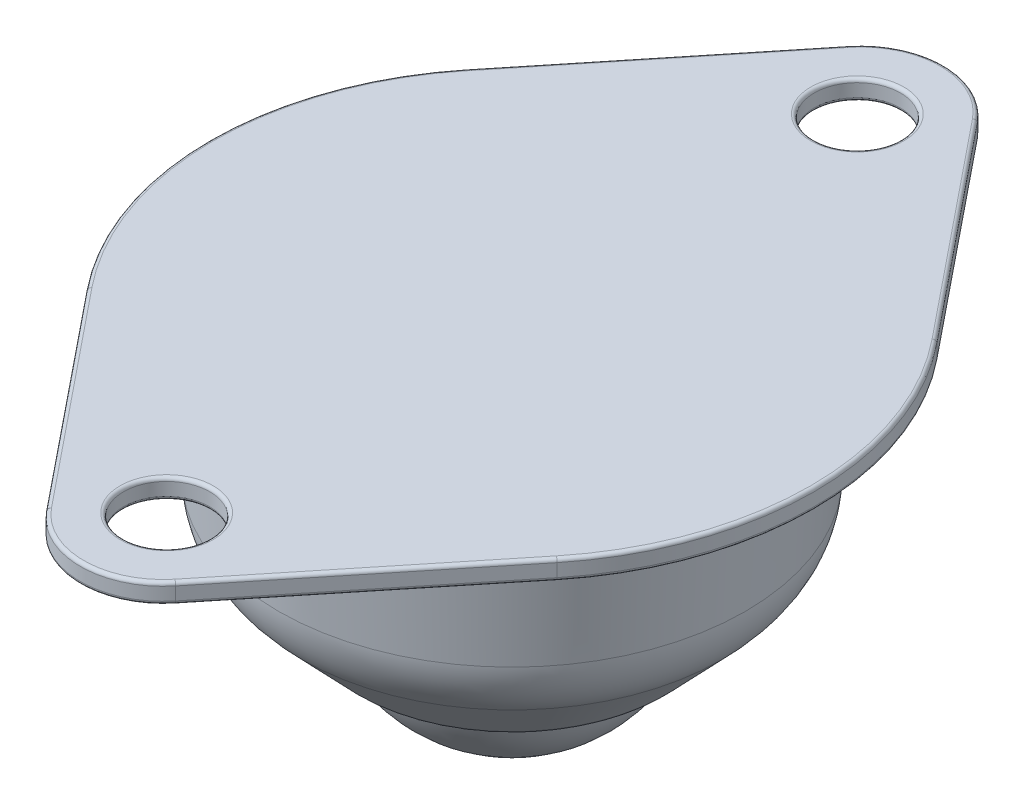
SolidWorks part; units mm, degrees
ref_plane "Front Plane" through (0, 0, 0) normal (0, 0, 1) x (1, 0, 0)
ref_plane "Top Plane" through (0, 0, 0) normal (0, 1, 0) x (1, 0, 0)
ref_plane "Right Plane" through (0, 0, 0) normal (1, 0, 0) x (0, 0, -1)
sketch "Sketch1" plane through (0, 0, 0) normal (0, 0, 1) x (1, 0, 0)
  line L0 (0, 0) -> (26, 0)
  line L1 (26, 0) -> (26, -1.15)
  line L2 (26, -1.15) -> (14, -1.15)
  line L3 (14, -1.15) -> (13.4, -10)
  line L4 (13.4, -10) -> (8.5993, -15)
  line L5 (8.5993, -15) -> (7.5993, -15)
  line L6 (0, -20.25) -> (0, 0) construction
  line L7 (0, 0) -> (0, -20.25)
  line L8 (0, -20.25) -> (1.9843, -20.25)
  arc A0 (7.5993, -15) -> (1.9843, -20.25) centre (0, -12.5) cw
  dimension "D1" = 8
  dimension "D2" = 12.5
  dimension "D3" = 1.15
  dimension "D4" = 26
  dimension "D5" = 13.4
  dimension "D6" = 10
  dimension "D7" = 1
  dimension "D8" = 15
  dimension "D9" = 14
  dimension "D10" = 20.25
revolve "Revolve1" add sketch "Sketch1" angle 360 about L6
fillet "Fillet1" radius 1 2 edges at (0, -1.15, -14) (0, -15, -8.5993)
fillet "Fillet2" radius 5 1 edges at (0, -10, -13.4)
sketch "Sketch2" plane through (0, 0, 0) normal (0, 1, 0) x (-1, 0, 0)
  line L0 (-28.5225, 0) -> (31.4876, 0) construction
  line L1 (0, 0) -> (0, -28.2647) construction
  line L2 (3.7327, -23.2178) -> (13.6087, -11.0025)
  line L3 (-3.7327, -23.2178) -> (-13.6087, -11.0025)
  line L4 (-3.7327, 23.2178) -> (-13.6087, 11.0025)
  line L5 (3.7327, 23.2178) -> (13.6087, 11.0025)
  line L7 (38.2676, -33.3146) -> (-40.1521, -33.3146)
  line L8 (38.2676, -33.3146) -> (38.2676, 32.2909)
  line L9 (38.2676, 32.2909) -> (-40.1521, 32.2909)
  line L10 (-40.1521, -33.3146) -> (-40.1521, 32.2909)
  arc A0 (-13.6087, 11.0025) -> (-13.6087, -11.0025) centre (0, 0) ccw
  arc A1 (13.6087, 11.0025) -> (13.6087, -11.0025) centre (0, 0) cw
  arc A2 (-3.7327, 23.2178) -> (3.7327, 23.2178) centre (0, 20.2) cw
  arc A4 (-3.7327, -23.2178) -> (3.7327, -23.2178) centre (0, -20.2) ccw
  dimension "D1" = 4.8
  dimension "D3" = 17.5
extrude "Extrude1" cut sketch "Sketch2" against normal blind 10
sketch "Sketch3" plane through (0, 0, 0) normal (0, 1, 0) x (1, 0, 0)
  line L0 (0, 17.5) -> (0, -17.5) construction
  circle A0 centre (0, 20) radius 2.5
  circle A1 centre (0, -20) radius 2.5
  dimension "D1" = 5
  dimension "D2" = 35
  dimension "D3" = 17.5
extrude "Extrude2" cut sketch "Sketch3" against normal blind 10
fillet "Fillet3" radius 0.2 20 edges at (8.6707, -1.15, 17.1101) (17.5, -1.15, 0) (8.6707, -1.15, -17.1101) (0, 0, 22.5) (0, -1.15, 17.5) (0, 0, -17.5) (0, -1.15, -22.5) (17.5, 0, 0) (8.6707, 0, -17.1101) (0, 0, -25) (-8.6707, 0, -17.1101) (-17.5, 0, 0) (-8.6707, 0, 17.1101) (0, 0, 25) (8.6707, 0, 17.1101) (0, -1.15, -25) (-8.6707, -1.15, -17.1101) (-17.5, -1.15, 0) (-8.6707, -1.15, 17.1101) (0, -1.15, 25)
